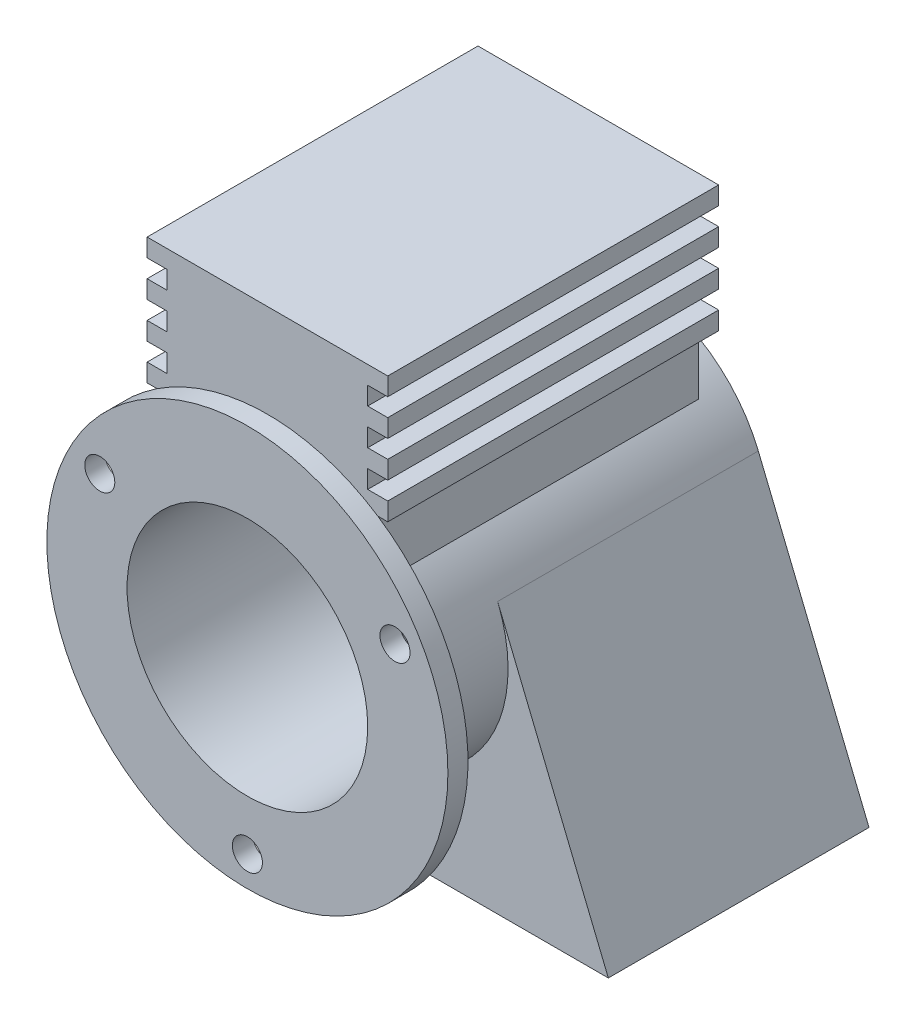
SolidWorks part; units mm, degrees
ref_plane "Front Plane" through (0, 0, 0) normal (0, 0, 1) x (1, 0, 0)
ref_plane "Top Plane" through (0, 0, 0) normal (0, 1, 0) x (1, 0, 0)
ref_plane "Right Plane" through (0, 0, 0) normal (1, 0, 0) x (0, 0, -1)
sketch "Sketch1" plane through (0, 0, 0) normal (0, 0, 1) x (1, 0, 0)
  line L0 (0, 0) -> (0, 266.0938) construction
  line L1 (-152.4, 0) -> (152.4, 0)
  line L2 (152.4, 0) -> (82.2851, 171.45)
  line L3 (-82.2851, 171.45) -> (-152.4, 0)
  arc A0 (82.2851, 171.45) -> (-82.2851, 171.45) centre (0, 137.7993) ccw
  dimension "D3" = 88.9
  dimension "D1" = 304.8
  dimension "D2" = 152.4
  dimension "D4" = 171.45
extrude "Boss-Extrude1" add sketch "Sketch1" along normal blind 165.1
sketch "Sketch2" plane through (0, 0, 165.1) normal (0, 0, 1) x (1, 0, 0)
  circle A0 centre (0, 137.7993) radius 88.9
  arc A1 (82.2851, 171.45) -> (-82.2851, 171.45) centre (0, 137.7993) ccw construction
  dimension "D1" = 177.8
extrude "Boss-Extrude2" add sketch "Sketch2" along normal blind 63.5
sketch "Sketch3" plane through (0, 0, 228.6) normal (0, 0, 1) x (1, 0, 0)
  circle A0 centre (0, 137.7993) radius 127
  circle A1 centre (0, 137.7993) radius 88.9 construction
  dimension "D1" = 254
extrude "Boss-Extrude3" add sketch "Sketch3" along normal blind 12.7
ref_plane "Plane1" through (0, 0, 19.05) normal (0, 0, -1) x (-1, 0, 0)
sketch "Sketch4" plane through (0, 0, 19.05) normal (0, 0, -1) x (-1, 0, 0)
  line L0 (-63.5, 189.5701) -> (-63.5, 243.84)
  line L1 (-63.5, 243.84) -> (-76.2, 243.84)
  line L2 (-76.2, 243.84) -> (-76.2, 255.27)
  line L3 (-76.2, 255.27) -> (-63.5, 255.27)
  line L4 (-63.5, 255.27) -> (-63.5, 266.7)
  line L5 (-63.5, 266.7) -> (-76.2, 266.7)
  line L6 (-76.2, 266.7) -> (-76.2, 278.13)
  line L7 (-76.2, 278.13) -> (-63.5, 278.13)
  line L8 (-63.5, 278.13) -> (-63.5, 289.56)
  line L9 (-63.5, 289.56) -> (-76.2, 289.56)
  line L10 (-76.2, 289.56) -> (-76.2, 300.99)
  line L11 (-76.2, 300.99) -> (-63.5, 300.99)
  line L12 (-63.5, 300.99) -> (-63.5, 312.42)
  line L13 (0, 0) -> (0, 286.2615) construction
  line L14 (-63.5, 312.42) -> (-76.2, 312.42)
  line L15 (-76.2, 312.42) -> (-76.2, 323.85)
  line L16 (-76.2, 323.85) -> (76.2, 323.85)
  line L17 (152.4, 0) -> (-152.4, 0) construction
  line L20 (76.2, 312.42) -> (76.2, 323.85)
  line L21 (63.5, 312.42) -> (76.2, 312.42)
  line L22 (63.5, 300.99) -> (63.5, 312.42)
  line L23 (76.2, 300.99) -> (63.5, 300.99)
  line L24 (76.2, 289.56) -> (76.2, 300.99)
  line L25 (63.5, 289.56) -> (76.2, 289.56)
  line L26 (63.5, 278.13) -> (63.5, 289.56)
  line L27 (76.2, 278.13) -> (63.5, 278.13)
  line L28 (76.2, 266.7) -> (76.2, 278.13)
  line L29 (63.5, 266.7) -> (76.2, 266.7)
  line L30 (63.5, 255.27) -> (63.5, 266.7)
  line L31 (76.2, 255.27) -> (63.5, 255.27)
  line L32 (76.2, 243.84) -> (76.2, 255.27)
  line L33 (63.5, 243.84) -> (76.2, 243.84)
  line L34 (63.5, 189.5701) -> (63.5, 243.84)
  arc A0 (-63.5, 189.5701) -> (63.5, 189.5701) centre (0, 137.7993) cw
  circle A1 centre (0, 137.7993) radius 88.9 construction
  point P28 (0, 323.85)
  dimension "D1" = 76.2
  dimension "D2" = 12.7
  dimension "D3" = 11.43
  dimension "D4" = 323.85
extrude "Boss-Extrude4" add sketch "Sketch4" against normal up to surface (209.55 mm away) up to face at (88.9, 137.7993, 228.6)
sketch "Sketch6" plane through (0, 0, 241.3) normal (0, 0, 1) x (1, 0, 0)
  circle A0 centre (0, 137.7993) radius 76.2
  circle A1 centre (0, 137.7993) radius 127 construction
  dimension "D1" = 152.4
extrude "Cut-Extrude1" cut sketch "Sketch6" against normal blind 228.6
sketch "Sketch7" plane through (0, 0, 0) normal (0, 0, -1) x (-1, 0, 0)
  circle A0 centre (0, 137.7993) radius 19.05
  arc A2 (82.2851, 171.45) -> (-82.2851, 171.45) centre (0, 137.7993) ccw construction
  dimension "D1" = 38.1
extrude "Cut-Extrude2" cut sketch "Sketch7" against normal up to next
sketch "Sketch9" plane through (0, 0, 241.3) normal (0, 0, 1) x (1, 0, 0)
  line L0 (0, 156.8493) -> (0, 10.7993) construction
  circle A0 centre (0, 29.8493) radius 9.525
  circle A1 centre (0, 137.7993) radius 19.05 construction
  circle A3 centre (0, 137.7993) radius 127 construction
  point P4 (0, 137.7993)
  dimension "D1" = 19.05
  dimension "D2" = 107.95
extrude "Cut-Extrude3" cut sketch "Sketch9" against normal up to next
pattern_circular "CirPattern1" count 3 over 360 about axis through (0, 137.7993, 0) along (0, 0, 1) of "Cut-Extrude3"
